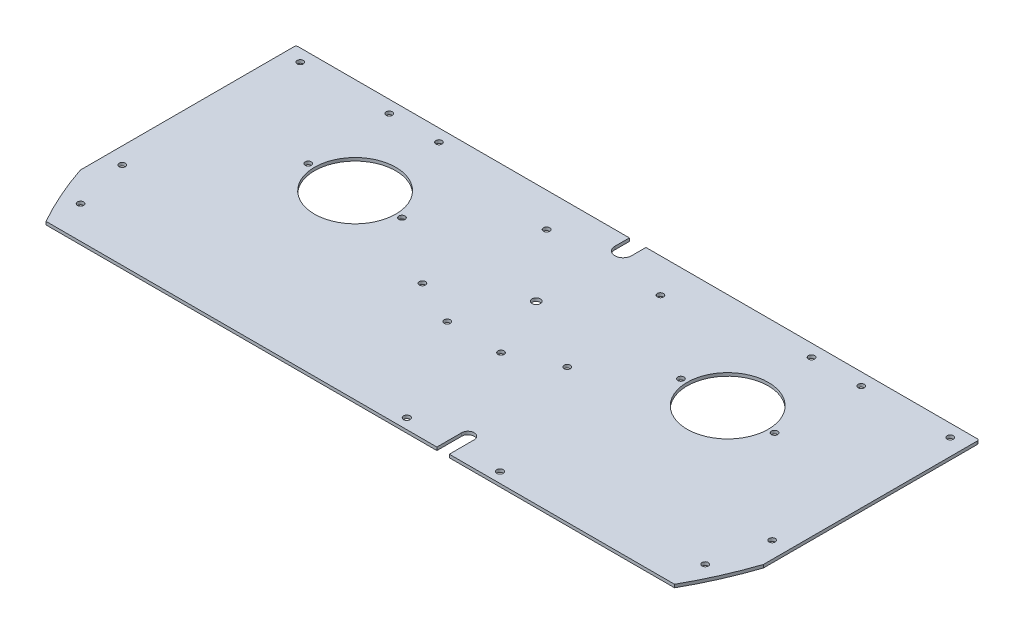
SolidWorks part; units mm, degrees
material "3.3535 (EN-AW 5754)"
ref_plane "Plan de face" through (0, 0, 0) normal (0, 0, 1) x (1, 0, 0)
ref_plane "Plan de dessus" through (0, 0, 0) normal (0, 1, 0) x (1, 0, 0)
ref_plane "Plan de droite" through (0, 0, 0) normal (1, 0, 0) x (0, 0, -1)
sketch "Esquisse1" plane through (0, 0, 0) normal (0, 1, 0) x (1, 0, 0)
  line L1 (0, 49) -> (165, 49)
  line L2 (0, 49) -> (0, -160)
  line L3 (0, -160) -> (68.3813, -160)
  line L4 (165, 49) -> (165, -55.2359)
  arc A0 (68.3813, -160) -> (165, -55.2359) centre (0, 0) ccw
  dimension "D4" = 348
  dimension "D1" = 49
  dimension "D2" = 165
  dimension "D3" = 160
extrude "Boss.-Extru.1" add sketch "Esquisse1" along normal blind 1.5
mirror "Symétrie1" about plane through (0, 1.5, -49) normal (1, 0, 0) of bodies 101 102
sketch "Esquisse7" plane through (0, 1.5, 0) normal (0, 1, 0) x (1, 0, 0)
  line L0 (-68.3813, -160) -> (68.3813, -160) construction
  line L1 (-165, -55.2359) -> (-165, 49) construction
  line L2 (165, -55.2359) -> (165, 49) construction
  line L3 (0, -0.825) -> (0, 0.825) construction
  line L4 (165, 49) -> (-165, 49) construction
  circle A0 centre (-157, -43) radius 1.5
  circle A1 centre (157, -43) radius 1.5
  circle A5 centre (157, 43) radius 1.5
  circle A13 centre (-157, 43) radius 1.5
  circle A14 centre (-114, 43) radius 1.5
  circle A15 centre (-90, 43) radius 1.5
  circle A16 centre (90, 43) radius 1.5
  circle A17 centre (114, 43) radius 1.5
  dimension "D5" = 3
  dimension "D3" = 43
  dimension "D4" = 86
  dimension "D8" = 117
  dimension "D9" = 8
  dimension "D6" = 8
  dimension "D7" = 24
  dimension "D10" = 180
  dimension "D11" = 6
  dimension "D12" = 90
  dimension "D13" = 114
  dimension "D1" = 2
  dimension "D2" = 2
extrude "Enlèv. mat.-Extru.5" cut sketch "Esquisse7" against normal through all
sketch "Esquisse8" plane through (0, 1.5, 0) normal (0, 1, 0) x (1, 0, 0)
  line L1 (0, -0.825) -> (0, 0.825) construction
  line L2 (-112.6274, 2.5) -> (-67.3726, 2.5) construction
  line L3 (-112.6274, 2.5) -> (-90, 25.1274) construction
  line L4 (-90, 25.1274) -> (-67.3726, 2.5) construction
  circle A1 centre (-90, 2.5) radius 19.6274
  circle A5 centre (-112.6274, 2.5) radius 1.5
  circle A6 centre (-67.3726, 2.5) radius 1.5
  circle A7 centre (112.6274, 2.5) radius 1.5
  circle A8 centre (67.3726, 2.5) radius 1.5
  circle A9 centre (-112.6274, 2.5) radius 3 construction
  circle A10 centre (90, 2.5) radius 19.6274
  dimension "D1" = 39.2548
  dimension "D2" = 3
  dimension "D3" = 45.2548
  dimension "D7" = 6
  dimension "D4" = 180
  dimension "D5" = 2.5
  dimension "D6" = 32
extrude "Enlèv. mat.-Extru.6" cut sketch "Esquisse8" against normal through all
sketch "Esquisse9" plane through (0, 1.5, 0) normal (0, 1, 0) x (1, 0, 0)
  line L0 (0, 49) -> (0, 42) construction
  line L1 (0, -0.825) -> (0, 0.825) construction
  line L2 (165, 49) -> (-165, 49) construction
  line L3 (4, 49) -> (4, 42)
  line L4 (-4, 49) -> (-4, 42)
  circle A1 centre (27.5, 32.5) radius 1.5
  circle A2 centre (-13, -30) radius 1.5
  circle A3 centre (35, -20) radius 1.5
  circle A4 centre (-27.5, 32.5) radius 1.5
  circle A5 centre (0, 0) radius 2
  arc A6 (4, 49) -> (-4, 49) centre (0, 49) ccw
  arc A7 (-4, 42) -> (4, 42) centre (0, 42) ccw
  circle A8 centre (-35, -20) radius 1.5
  circle A9 centre (13, -30) radius 1.5
  point P17 (0, 45.5)
  dimension "D1" = 3
  dimension "D2" = 48
  dimension "D3" = 10
  dimension "D4" = 55
  dimension "D5" = 32.5
  dimension "D8" = 4
  dimension "D11" = 42
  dimension "D6" = 30
  dimension "D7" = 13
  dimension "D9" = 8
  dimension "D10" = 7
extrude "Enlèv. mat.-Extru.7" cut sketch "Esquisse9" against normal through all
sketch "Esquisse10" plane through (0, 1.5, 0) normal (0, 1, 0) x (1, 0, 0)
  line L0 (40, -73) -> (40, -150) construction
  line L1 (43, -73) -> (43, -150)
  line L2 (37, -73) -> (37, -150)
  arc A0 (43, -73) -> (37, -73) centre (40, -73) ccw
  arc A1 (37, -150) -> (43, -150) centre (40, -150) ccw
  point P2 (40, -111.5)
  dimension "D2" = 40
  dimension "D3" = 150
  dimension "D1" = 73
  dimension "D4" = 6
extrude "Enlèv. mat.-Extru.8" cut sketch "Esquisse10" against normal through all
fillet "Congé1" radius 1 2 edges at (165, 0.75, -49) (-165, 0.75, -49)
sketch "Esquisse11" plane through (0, 1.5, 0) normal (0, 1, 0) x (1, 0, 0)
  line L0 (0, -0.825) -> (0, 0.825) construction
  line L1 (-68.3813, -160) -> (68.3813, -160) construction
  circle A0 centre (-150.8698, -69.241) radius 1.5
  circle A1 centre (-116.4, -118.3514) radius 1.5
  circle A2 centre (-66.7233, -152) radius 1.5
  circle A3 centre (66.7233, -152) radius 1.5
  circle A4 centre (116.4, -118.3514) radius 1.5
  circle A5 centre (150.8698, -69.241) radius 1.5
  circle A6 centre (-15, -152) radius 1.5
  circle A7 centre (0, 0) radius 166 construction
  arc A8 (-165, -55.2359) -> (-68.3813, -160) centre (0, 0) ccw construction
  circle A9 centre (15, -152) radius 1.5
  dimension "D1" = 8
  dimension "D2" = 8
  dimension "D3" = 3
  dimension "D4" = 60
  dimension "D5" = 60
  dimension "D6" = 51.7233
  dimension "D7" = 30
extrude "Enlèv. mat.-Extru.9" cut sketch "Esquisse11" against normal through all
sketch "Esquisse12" plane through (0, 1.5, 0) normal (0, 1, 0) x (1, 0, 0)
  line L0 (-165, -55.2359) -> (-165, 48) construction
  line L1 (-165, -85) -> (165, -85)
  line L2 (-165, -85) -> (-165, -160)
  line L3 (-165, -160) -> (165, -160)
  line L4 (165, -85) -> (165, -160)
  line L5 (165, -55.2359) -> (165, 48) construction
  line L6 (-68.3813, -160) -> (68.3813, -160) construction
  line L7 (17.5, -80) -> (62.5, -80) construction
  circle A0 centre (17.5, -80) radius 1.6
  circle A1 centre (62.5, -80) radius 1.6
  point P15 (40, -80)
  dimension "D2" = 3.2
  dimension "D1" = 85
  dimension "D3" = 45
  dimension "D4" = 40
  dimension "D5" = 80
extrude "Enlèv. mat.-Extru.10" cut sketch "Esquisse12" against normal through all
equation "\"D3@Esquisse7\"=\"D4@Esquisse7\"*(\"D2@Esquisse7\"-1)/2"
equation "\"D6@Esquisse7\"=\"D9@Esquisse7\""
